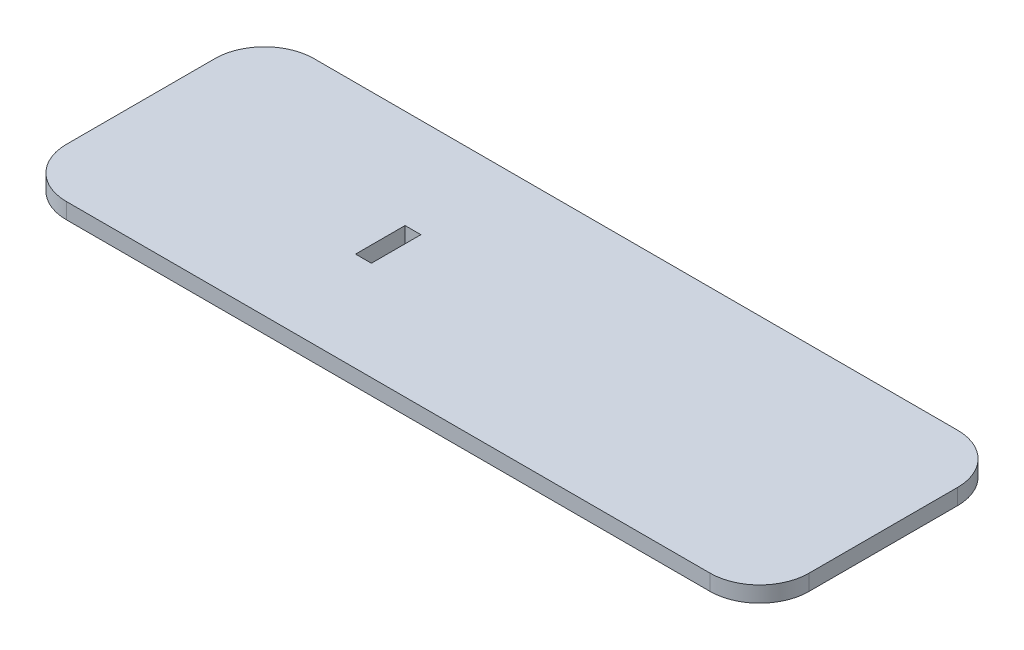
SolidWorks part; units mm, degrees
material "Oak"
ref_plane "Front Plane" through (0, 0, 0) normal (0, 0, 1) x (1, 0, 0)
ref_plane "Top Plane" through (0, 0, 0) normal (0, 1, 0) x (1, 0, 0)
ref_plane "Right Plane" through (0, 0, 0) normal (1, 0, 0) x (0, 0, -1)
sketch "Base_Sketch" plane through (0, 0, 0) normal (0, 1, 0) x (1, 0, 0)
  line L0 (-75, 0) -> (-25, 0) construction
  line L1 (-75, 25) -> (75, 25)
  line L2 (-75, 25) -> (-75, -25)
  line L3 (-75, -25) -> (75, -25)
  line L4 (75, 25) -> (75, -25)
  line L5 (-75, 25) -> (75, -25) construction
  line L6 (-75, -25) -> (75, 25) construction
  line L7 (-25, 0) -> (25, 0) construction
  line L8 (25, 0) -> (75, 0) construction
  line L10 (-26.6, 5) -> (-23.4, 5)
  line L11 (-26.6, 5) -> (-26.6, -5)
  line L12 (-26.6, -5) -> (-23.4, -5)
  line L13 (-23.4, 5) -> (-23.4, -5)
  line L14 (-26.6, 5) -> (-23.4, -5) construction
  line L15 (-26.6, -5) -> (-23.4, 5) construction
  point P0 (0, 0)
  dimension "D1" = 50
  dimension "D2" = 150
  dimension "D3" = 3.2
  dimension "D4" = 10
extrude "Boss-Extrude1" add sketch "Base_Sketch" along normal blind 3.2
fillet "Fillet1" radius 10 4 edges at (75, 1.6, -25) (75, 1.6, 25) (-75, 1.6, -25) (-75, 1.6, 25)
equation "\"Material_Thickness\"= \"Material_Thickness@Soldering_Jig.Assembly\""
equation "\"D3@Base_Sketch\" = \"Material_Thickness\""
equation "\"D1@Boss-Extrude1\"=\"Material_Thickness\""
